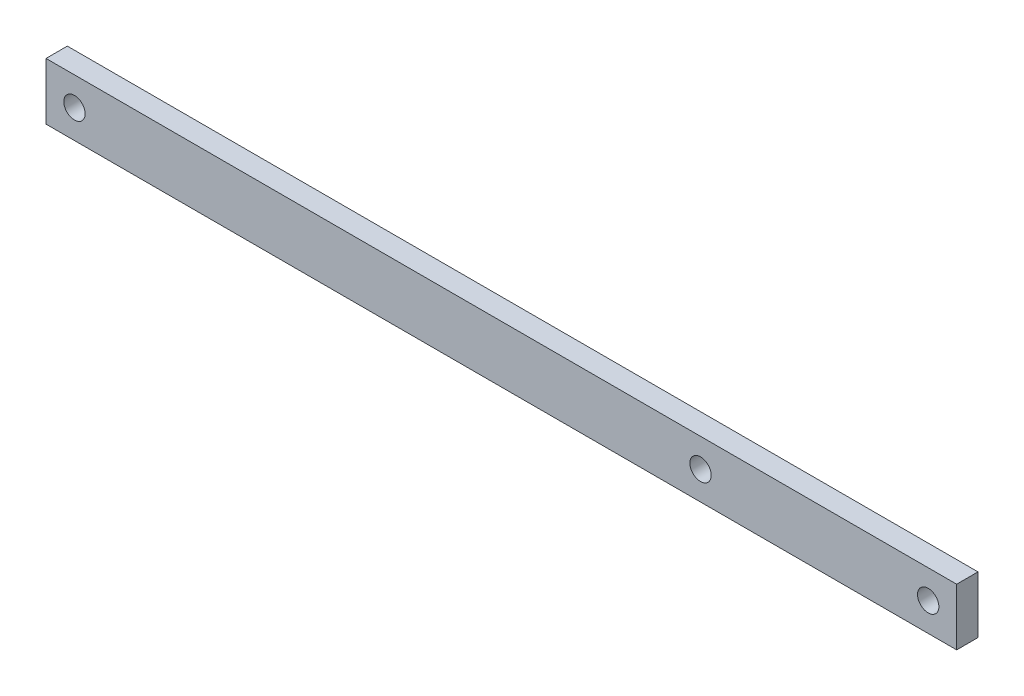
SolidWorks part; units mm, degrees
ref_plane "Front Plane" through (0, 0, 0) normal (0, 0, 1) x (1, 0, 0)
ref_plane "Top Plane" through (0, 0, 0) normal (0, 1, 0) x (1, 0, 0)
ref_plane "Right Plane" through (0, 0, 0) normal (1, 0, 0) x (0, 0, -1)
sketch "Sketch1" plane through (0, 0, 0) normal (0, 0, 1) x (1, 0, 0)
  line L1 (101.6, -6.35) -> (-101.6, -6.35)
  line L2 (101.6, -6.35) -> (101.6, 6.35)
  line L3 (101.6, 6.35) -> (-101.6, 6.35)
  line L4 (-101.6, -6.35) -> (-101.6, 6.35)
  line L5 (101.6, -6.35) -> (-101.6, 6.35) construction
  line L6 (101.6, 6.35) -> (-101.6, -6.35) construction
  circle A0 centre (95.25, 0) radius 2.3813
  circle A1 centre (44.45, 0) radius 2.3812
  circle A2 centre (-95.25, 0) radius 2.3813
  point P0 (0, 0)
  point P12 (0, 0)
  dimension "D3" = 4.7625
  dimension "D4" = 4.7625
  dimension "D5" = 4.7625
  dimension "D1" = 203.2
  dimension "D2" = 12.7
  dimension "D6" = 6.35
  dimension "D7" = 6.35
  dimension "D8" = 57.15
extrude "Boss-Extrude1" add sketch "Sketch1" along normal blind 4.7625
